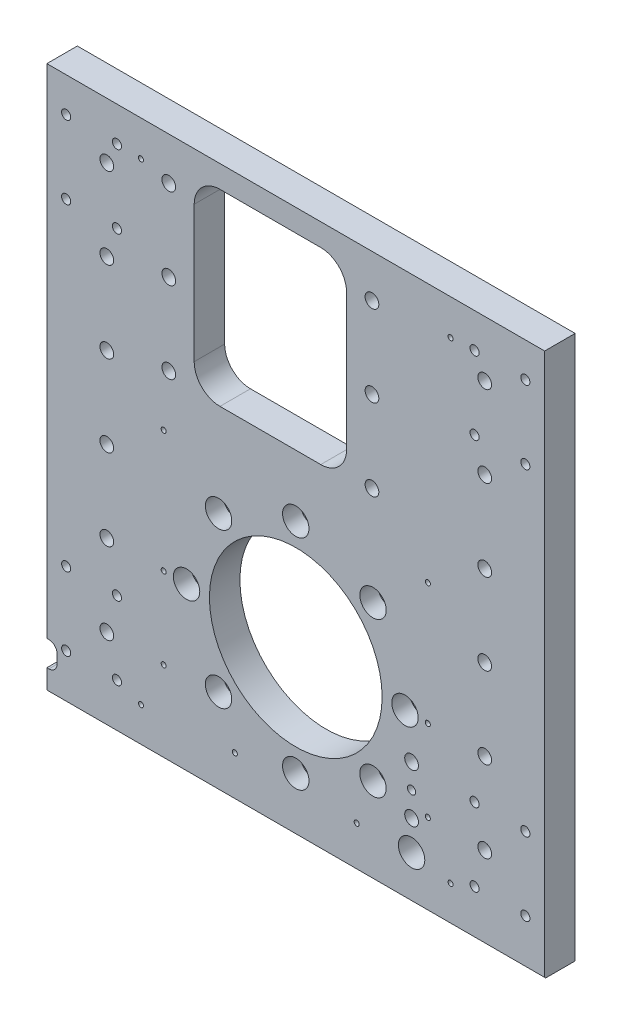
SolidWorks part; units mm, degrees
material "Low Carbon Steel"
ref_plane "Front Plane" through (0, 0, 0) normal (0, 0, 1) x (1, 0, 0)
ref_plane "Top Plane" through (0, 0, 0) normal (0, 1, 0) x (1, 0, 0)
ref_plane "Right Plane" through (0, 0, 0) normal (1, 0, 0) x (0, 0, -1)
sketch "Sketch1" plane through (0, 0, 0) normal (0, 0, 1) x (1, 0, 0)
  line L0 (0, 0) -> (0, -160) construction
  line L1 (-245, 375) -> (245, 375)
  line L2 (-245, 375) -> (-245, -160)
  line L3 (-245, -160) -> (245, -160)
  line L4 (245, 375) -> (245, -160)
  dimension "D1" = 490
  dimension "D2" = 160
  dimension "D3" = 535
extrude "Boss-Extrude1" add sketch "Sketch1" along normal mid plane 38.1
sketch "Sketch2" plane through (0, 375, 0) normal (0, 1, 0) x (1, 0, 0)
  line L0 (245, -19.05) -> (245, 19.05) construction
  line L1 (-245, 19.05) -> (245, 19.05)
  line L2 (-245, 19.05) -> (-245, 15)
  line L3 (-245, 15) -> (245, 15)
  line L4 (245, 19.05) -> (245, 15)
  line L5 (-245, -19.05) -> (-245, 19.05) construction
  line L6 (245, -19.05) -> (-245, -19.05)
  line L7 (245, -19.05) -> (245, -15)
  line L8 (245, -15) -> (-245, -15)
  line L9 (-245, -19.05) -> (-245, -15)
  dimension "D1" = 30
extrude "Cut-Extrude1" cut sketch "Sketch2" against normal through all
sketch "Sketch3" plane through (0, 0, 15) normal (0, 0, 1) x (1, 0, 0)
  circle A0 centre (0, 0) radius 85
  dimension "D1" = 170
extrude "Cut-Extrude2" cut sketch "Sketch3" against normal through all
hole_wizard "CBORE for M16 Hex Socket Head Cap Screw1" positions "Sketch7" profile "Sketch6" counterbore size "M16" standard "Peddi DIN" end condition through all
sketch "Sketch7" plane through (0, 0, 15) normal (0, 0, 1) x (1, 0, 0)
  line L2 (76.014, 76.014) -> (0, 107.5) construction
  line L3 (0, 107.5) -> (-76.014, 76.014) construction
  line L4 (-76.014, 76.014) -> (-107.5, 0) construction
  line L5 (-107.5, 0) -> (-76.014, -76.014) construction
  line L6 (-76.014, -76.014) -> (0, -107.5) construction
  line L7 (0, -107.5) -> (76.014, -76.014) construction
  line L8 (76.014, -76.014) -> (107.5, 0) construction
  line L9 (107.5, 0) -> (76.014, 76.014) construction
  line L10 (107.5, 0) -> (107.5, 76.014) construction
  line L11 (0, 107.5) -> (0, 0) construction
  circle A1 centre (0, 0) radius 107.5 construction
  circle A2 centre (0, 0) radius 99.317 construction
  point P0 (0, 107.5)
  point P14 (76.014, 76.014)
  point P16 (-76.014, 76.014)
  point P17 (-107.5, 0)
  point P18 (-76.014, -76.014)
  point P19 (0, -107.5)
  point P20 (76.014, -76.014)
  point P21 (107.5, 0)
  dimension "D1" = 215
sketch "Sketch6" plane through (0, 107.5, 15) normal (1, 0, 0) x (0, -1, 0)
  line L0 (0, 0) -> (0, 30)
  line L1 (0, 30) -> (8.75, 30)
  line L3 (8.75, 30) -> (8.75, 17.5)
  line L4 (8.75, 17.5) -> (13, 17.5)
  line L5 (13, 17.5) -> (13, 0)
  line L7 (13, 0) -> (0, 0)
  line L11 (0, -6.35) -> (0, 107.95) construction
  dimension "Thru Hole Dia." = 17.5
  dimension "Thru Hole Depth" = 30
  dimension "C'Bore Dia." = 26
  dimension "C'Bore Depth" = 17.5
hole_wizard "CBORE for M8 Hex Socket Head Cap Screw1" positions "Sketch10" profile "Sketch9" counterbore size "M8" standard "Peddi DIN" end condition through all
sketch "Sketch10" plane through (0, 0, -15) normal (0, 0, -1) x (-1, 0, 0)
  line L0 (176, -44) -> (176, -116) construction
  line L1 (176, -116) -> (226, -116) construction
  line L2 (226, -116) -> (226, -44) construction
  line L3 (226, -44) -> (176, -44) construction
  line L5 (201, -44) -> (201, -116) construction
  line L7 (226, -80) -> (176, -80) construction
  line L8 (-226, -116) -> (-176, -116) construction
  line L9 (-176, -116) -> (-176, -44) construction
  line L10 (-176, -44) -> (-226, -44) construction
  line L11 (-226, -44) -> (-226, -116) construction
  line L13 (176, -116) -> (0, -116) construction
  line L14 (0, -116) -> (-176, -116) construction
  line L16 (0, -116) -> (0, 0) construction
  line L19 (-226, 341) -> (-176, 341) construction
  line L20 (-226, 341) -> (-226, 269) construction
  line L21 (-226, 269) -> (-176, 269) construction
  line L22 (-176, 341) -> (-176, 269) construction
  line L24 (176, 341) -> (226, 341) construction
  line L25 (176, 341) -> (176, 269) construction
  line L26 (176, 269) -> (226, 269) construction
  line L27 (226, 341) -> (226, 269) construction
  circle A0 centre (0, 0) radius 85 construction
  point P0 (226, -116)
  point P2 (176, -116)
  point P4 (176, -44)
  point P6 (226, -44)
  point P28 (-226, -44)
  point P30 (-176, -44)
  point P32 (-176, -116)
  point P34 (-226, -116)
  point P60 (-226, 341)
  point P61 (-176, 269)
  point P64 (-226, 269)
  point P65 (-176, 341)
  point P126 (176, 341)
  point P127 (226, 269)
  point P130 (176, 269)
  point P131 (226, 341)
  dimension "D1" = 201
  dimension "D2" = 72
  dimension "D3" = 50
  dimension "D4" = 80
  dimension "D5" = 385
sketch "Sketch9" plane through (-226, -116, -15) normal (1, 0, 0) x (0, 1, 0)
  line L0 (0, 0) -> (0, 30)
  line L1 (0, 30) -> (4.5, 30)
  line L3 (4.5, 30) -> (4.5, 9)
  line L4 (4.5, 9) -> (7.5, 9)
  line L5 (7.5, 9) -> (7.5, 0)
  line L7 (7.5, 0) -> (0, 0)
  line L11 (0, -6.35) -> (0, 107.95) construction
  dimension "Thru Hole Dia." = 9
  dimension "Thru Hole Depth" = 30
  dimension "C'Bore Dia." = 15
  dimension "C'Bore Depth" = 9
hole_wizard "CBORE for M12 Hex Socket Head Cap Screw1" positions "Sketch12" profile "Sketch11" counterbore size "M12" standard "Peddi DIN" end condition through all
sketch "Sketch12" plane through (0, 0, -15) normal (0, 0, -1) x (-1, 0, 0)
  line L0 (125, 173) -> (-75, 173) construction
  line L3 (0, 0) -> (0, 107.5) construction
  line L5 (125, 173) -> (125, 253) construction
  line L6 (125, 253) -> (125, 333) construction
  line L8 (-75, 173) -> (-75, 253) construction
  line L9 (-75, 253) -> (-75, 333) construction
  line L10 (25, 173) -> (25, 107.5) construction
  line L12 (0, 107.5) -> (25, 107.5) construction
  line L13 (-114, -40.74) -> (-114, -88.74) construction
  circle A0 centre (0, 0) radius 85 construction
  point P0 (-75, 173)
  point P2 (125, 173)
  point P19 (125, 253)
  point P21 (125, 333)
  point P26 (-75, 253)
  point P28 (-75, 333)
  dimension "D1" = 173
  dimension "D6" = 40.74
  dimension "D2" = 200
  dimension "D3" = 80
  dimension "D4" = 25
  dimension "D5" = 114
  dimension "D7" = 48
  dimension "D8" = 80
sketch "Sketch11" plane through (75, 173, -15) normal (1, 0, 0) x (0, 1, 0)
  line L0 (0, 0) -> (0, 30)
  line L1 (0, 30) -> (6.75, 30)
  line L3 (6.75, 30) -> (6.75, 13)
  line L4 (6.75, 13) -> (10, 13)
  line L5 (10, 13) -> (10, 0)
  line L7 (10, 0) -> (0, 0)
  line L11 (0, -6.35) -> (0, 107.95) construction
  dimension "Thru Hole Dia." = 13.5
  dimension "Thru Hole Depth" = 30
  dimension "C'Bore Dia." = 20
  dimension "C'Bore Depth" = 13
hole_wizard "CBORE for M12 Hex Socket Head Cap Screw3" positions "Sketch33" profile "Sketch34" counterbore size "M12" standard "Peddi DIN" end condition through all
sketch "Sketch33" plane through (0, 0, -15) normal (0, 0, -1) x (-1, 0, 0)
  point P0 (-114, -40.74)
  point P3 (-114, -88.74)
sketch "Sketch34" plane through (114, -40.74, -15) normal (1, 0, 0) x (0, 1, 0)
  line L0 (0, 0) -> (0, 30)
  line L1 (0, 30) -> (6.75, 30)
  line L3 (6.75, 30) -> (6.75, 13)
  line L4 (6.75, 13) -> (10, 13)
  line L5 (10, 13) -> (10, 0)
  line L7 (10, 0) -> (0, 0)
  line L11 (0, -6.35) -> (0, 107.95) construction
  dimension "Thru Hole Dia." = 13.5
  dimension "Thru Hole Depth" = 30
  dimension "C'Bore Dia." = 20
  dimension "C'Bore Depth" = 13
hole_wizard "Ø8.0 (8) Diameter Hole1" positions "Sketch14" profile "Sketch13" hole size "Ø8.0" standard "Peddi DIN" end condition through all
sketch "Sketch14" plane through (0, 0, -15) normal (0, 0, -1) x (-1, 0, 0)
  line L0 (-114, -40.74) -> (-114, -88.74) construction
  point P0 (-114, -64.74)
sketch "Sketch13" plane through (114, -64.74, -15) normal (1, 0, 0) x (0, 1, 0)
  line L0 (0, 0) -> (0, 30)
  line L1 (0, 30) -> (4, 30)
  line L2 (4, 30) -> (4, 0)
  line L5 (4, 0) -> (0, 0)
  line L11 (0, -6.35) -> (0, 107.95) construction
  dimension "Thru Hole Dia." = 8
  dimension "Thru Hole Depth" = 30
hole_wizard "M6 Tapped Hole1" positions "Sketch19" profile "Sketch18" tap size "M6" standard "Peddi DIN"
sketch "Sketch19" plane through (0, 0, 15) normal (0, 0, -1) x (-1, 0, 0)
  line L1 (0, 0) -> (-130, 0) construction
  line L2 (-130, 0) -> (-130, 120) construction
  line L5 (-130, 0) -> (-130, -80) construction
  line L8 (0, 0) -> (0, -120) construction
  line L9 (0, -120) -> (-60, -120) construction
  line L12 (0, -120) -> (60, -120) construction
  line L15 (0, 0) -> (130, 0) construction
  line L16 (130, 0) -> (130, 120) construction
  line L19 (130, 0) -> (130, -80) construction
  point P0 (-130, -80)
  point P48 (-60, -120)
  point P51 (60, -120)
  point P54 (130, -80)
  point P57 (130, 0)
  point P60 (130, 120)
  point P63 (-130, 120)
  point P66 (-130, 0)
  dimension "D1" = 120
  dimension "D2" = 120
  dimension "D3" = 70
  dimension "D4" = 80
  dimension "D5" = 120
cosmetic thread "Hole Thread15" parameters "D1"=15.01, "D2"=6
cosmetic thread "Hole Thread16" parameters "D1"=15.01, "D2"=6
cosmetic thread "Hole Thread17" parameters "D1"=15.01, "D2"=6
cosmetic thread "Hole Thread18" parameters "D1"=15.01, "D2"=6
cosmetic thread "Hole Thread19" parameters "D1"=15.01, "D2"=6
cosmetic thread "Hole Thread20" parameters "D1"=15.01, "D2"=6
cosmetic thread "Hole Thread21" parameters "D1"=15.01, "D2"=6
cosmetic thread "Hole Thread22" parameters "D1"=10, "D2"=6
sketch "Sketch18" plane through (130, -80, 15) normal (1, 0, 0) x (0, -1, 0)
  line L0 (0, 0) -> (0, 21.5122)
  line L1 (0, 21.5122) -> (2.5, 20.01)
  line L2 (2.5, 20.01) -> (2.5, 0)
  line L5 (2.5, 0) -> (0, 0)
  line L10 (0, 21.5122) -> (-2.5, 20.01) construction
  line L11 (0, -6.35) -> (0, 107.95) construction
  dimension "Tap Drill Dia." = 5
  dimension "Tap Drill Depth" = 20.01
  dimension "Drill Angle" = 118
hole_wizard "Ø13.5 (13.5) Diameter Hole3" positions "Sketch21" profile "Sketch20" hole size "Ø13.5" standard "Peddi DIN"
sketch "Sketch21" plane through (0, 0, -15) normal (0, 0, -1) x (-1, 0, 0)
  point P0 (-114, -64.74)
  point P3 (-130, -80)
sketch "Sketch20" plane through (114, -64.74, -15) normal (1, 0, 0) x (0, 1, 0)
  line L0 (0, 0) -> (0, 19.0558)
  line L1 (0, 19.0558) -> (6.75, 15)
  line L2 (6.75, 15) -> (6.75, 0)
  line L5 (6.75, 0) -> (0, 0)
  line L10 (0, 19.0558) -> (-6.75, 15) construction
  line L11 (0, -6.35) -> (0, 107.95) construction
  dimension "Hole Dia." = 13.5
  dimension "Hole Depth" = 15
  dimension "Drill Angle" = 118
sketch "Sketch24" plane through (0, 0, -15) normal (0, 0, -1) x (-1, 0, 0)
  line L0 (25, 253) -> (25, 168) construction
  line L1 (25, 253) -> (25, 353) construction
  line L5 (-75, 253) -> (125, 253) construction
  line L6 (-24.6, 353) -> (74.6, 353)
  line L7 (-50, 327.6) -> (-50, 193.4)
  line L8 (-24.6, 168) -> (74.6, 168)
  line L9 (100, 327.6) -> (100, 193.4)
  arc A0 (-50, 193.4) -> (-24.6, 168) centre (-24.6, 193.4) ccw
  arc A1 (74.6, 353) -> (100, 327.6) centre (74.6, 327.6) cw
  circle A2 centre (0, 0) radius 85 construction
  arc A3 (-24.6, 353) -> (-50, 327.6) centre (-24.6, 327.6) ccw
  arc A4 (74.6, 168) -> (100, 193.4) centre (74.6, 193.4) ccw
  dimension "D4" = 25.4
  dimension "D1" = 150
  dimension "D2" = 185
  dimension "D3" = 168
extrude "Cut-Extrude6" cut sketch "Sketch24" against normal through all
hole_wizard "M6 Tapped Hole2" positions "Sketch26" profile "Sketch25" tap size "M6" standard "Peddi DIN"
sketch "Sketch26" plane through (0, 0, -15) normal (0, 0, -1) x (-1, 0, 0)
  line L0 (0, 0) -> (0, 327.5) construction
  line L2 (-226, 327.5) -> (226, 327.5) construction
  line L4 (226, 327.5) -> (226, 147.5) construction
  line L5 (226, 147.5) -> (226, -132.5) construction
  line L7 (-226, -132.5) -> (-226, 147.5) construction
  line L8 (-226, 147.5) -> (-226, 327.5) construction
  line L9 (245, 375) -> (-245, 375) construction
  line L10 (245, -160) -> (-245, -160) construction
  circle A0 centre (226, 341) radius 4.5 construction
  circle A1 centre (226, 341) radius 4.5 construction
  point P2 (226, 327.5)
  point P4 (-226, 327.5)
  point P6 (226, 147.5)
  point P8 (226, -132.5)
  point P10 (-226, -132.5)
  point P12 (-226, 147.5)
  dimension "D2" = 180
  dimension "D3" = 132.5
  dimension "D4" = 47.5
  dimension "D5" = 27.5
  dimension "D6" = 280
sketch "Sketch25" plane through (-226, 327.5, -15) normal (1, 0, 0) x (0, 1, 0)
  line L0 (0, 0) -> (0, 29.4922)
  line L1 (0, 29.4922) -> (2.5, 27.99)
  line L2 (2.5, 27.99) -> (2.5, 0)
  line L5 (2.5, 0) -> (0, 0)
  line L10 (0, 29.4922) -> (-2.5, 27.99) construction
  line L11 (0, -6.35) -> (0, 107.95) construction
  dimension "Tap Drill Dia." = 5
  dimension "Tap Drill Depth" = 27.99
  dimension "Drill Angle" = 118
cosmetic thread "Hole Thread2" parameters "D1"=15.01, "D2"=6
cosmetic thread "Hole Thread3" parameters "D1"=15.01, "D2"=6
cosmetic thread "Hole Thread4" parameters "D1"=15.01, "D2"=6
cosmetic thread "Hole Thread5" parameters "D1"=15.01, "D2"=6
cosmetic thread "Hole Thread6" parameters "D1"=15.01, "D2"=6
cosmetic thread "Hole Thread7" parameters "D1"=15.01, "D2"=6
hole_wizard "CBORE for M12 Hex Socket Head Cap Screw2" positions "Sketch27" profile "Sketch28" counterbore size "M12" standard "Peddi DIN" end condition through all
sketch "Sketch27" plane through (0, 0, -15) normal (0, 0, -1) x (-1, 0, 0)
  line L0 (-186, -80) -> (186, -80) construction
  line L3 (0, -80) -> (0, 0) construction
  line L4 (245, -160) -> (-245, -160) construction
  point P1 (-186, -80)
  point P2 (186, -80)
  dimension "D1" = 372
  dimension "D2" = 80
sketch "Sketch28" plane through (186, -80, -15) normal (1, 0, 0) x (0, 1, 0)
  line L0 (0, 0) -> (0, 30)
  line L1 (0, 30) -> (6.75, 30)
  line L3 (6.75, 30) -> (6.75, 13)
  line L4 (6.75, 13) -> (10, 13)
  line L5 (10, 13) -> (10, 0)
  line L7 (10, 0) -> (0, 0)
  line L11 (0, -6.35) -> (0, 107.95) construction
  dimension "Thru Hole Dia." = 13.5
  dimension "Thru Hole Depth" = 30
  dimension "C'Bore Dia." = 20
  dimension "C'Bore Depth" = 13
pattern_linear "LPattern1" count 6 spacing 80 along (0, 1, 0) of "CBORE for M12 Hex Socket Head Cap Screw2"
hole_wizard "Ø26.0 (26) Diameter Hole1" positions "Sketch29" profile "Sketch30" hole size "Ø26.0" standard "Peddi DIN" end condition through all
sketch "Sketch29" plane through (0, 0, -15) normal (0, 0, -1) x (-1, 0, 0)
  line L2 (-114, -88.74) -> (-114, -118) construction
  circle A0 centre (0, 0) radius 85 construction
  point P0 (-114, -118)
  dimension "D2" = 118
sketch "Sketch30" plane through (114, -118, -15) normal (1, 0, 0) x (0, 1, 0)
  line L0 (0, 0) -> (0, 30)
  line L1 (0, 30) -> (13, 30)
  line L2 (13, 30) -> (13, 0)
  line L5 (13, 0) -> (0, 0)
  line L11 (0, -6.35) -> (0, 107.95) construction
  dimension "Thru Hole Dia." = 26
  dimension "Thru Hole Depth" = 30
chamfer "Chamfer1" distance 1 angle 45 1 edges at (0, -160, 15)
hole_wizard "M6 Tapped Hole3" positions "Sketch31" profile "Sketch32" tap size "M6" standard "Peddi DIN"
sketch "Sketch31" plane through (0, 0, 15) normal (0, 0, 1) x (1, 0, 0)
  line L1 (-152.4, 340.075) -> (152.4, 340.075) construction
  line L2 (-152.4, 340.075) -> (-152.4, -125.075) construction
  line L3 (-152.4, -125.075) -> (152.4, -125.075) construction
  line L4 (152.4, 340.075) -> (152.4, -125.075) construction
  line L5 (0, 340.075) -> (0, 0) construction
  line L7 (245, 375) -> (-245, 375) construction
  line L9 (245, -160) -> (-245, -160) construction
  point P0 (-152.4, 340.075)
  point P1 (152.4, -125.075)
  point P136 (-152.4, -125.075)
  point P137 (152.4, 340.075)
  dimension "D1" = 34.925
  dimension "D2" = 34.925
  dimension "D3" = 304.8
sketch "Sketch32" plane through (-152.4, 340.075, 15) normal (1, 0, 0) x (0, -1, 0)
  line L0 (0, 0) -> (0, 29.4922)
  line L1 (0, 29.4922) -> (2.5, 27.99)
  line L2 (2.5, 27.99) -> (2.5, 0)
  line L5 (2.5, 0) -> (0, 0)
  line L10 (0, 29.4922) -> (-2.5, 27.99) construction
  line L11 (0, -6.35) -> (0, 107.95) construction
  dimension "Tap Drill Dia." = 5
  dimension "Tap Drill Depth" = 27.99
  dimension "Drill Angle" = 118
cosmetic thread "Hole Thread23" parameters "D1"=15.01, "D2"=6
cosmetic thread "Hole Thread24" parameters "D1"=15.01, "D2"=6
cosmetic thread "Hole Thread25" parameters "D1"=15.01, "D2"=6
cosmetic thread "Hole Thread26" parameters "D1"=15.01, "D2"=6
sketch "Sketch35" plane through (0, 0, -15) normal (0, 0, -1) x (-1, 0, 0)
  line L0 (245, -115) -> (243, -115)
  line L1 (245, -160) -> (245, 375) construction
  line L2 (235, -123) -> (235, -132)
  line L3 (243, -140) -> (245, -140)
  line L4 (245, -140) -> (245, -115)
  line L5 (245, -160) -> (-245, -160) construction
  arc A0 (235, -132) -> (243, -140) centre (243, -132) ccw
  arc A1 (243, -115) -> (235, -123) centre (243, -123) ccw
  dimension "D4" = 8
  dimension "D1" = 25
  dimension "D2" = 20
  dimension "D3" = 10
extrude "Cut-Extrude7" cut sketch "Sketch35" against normal through all
other "Freeze***"
